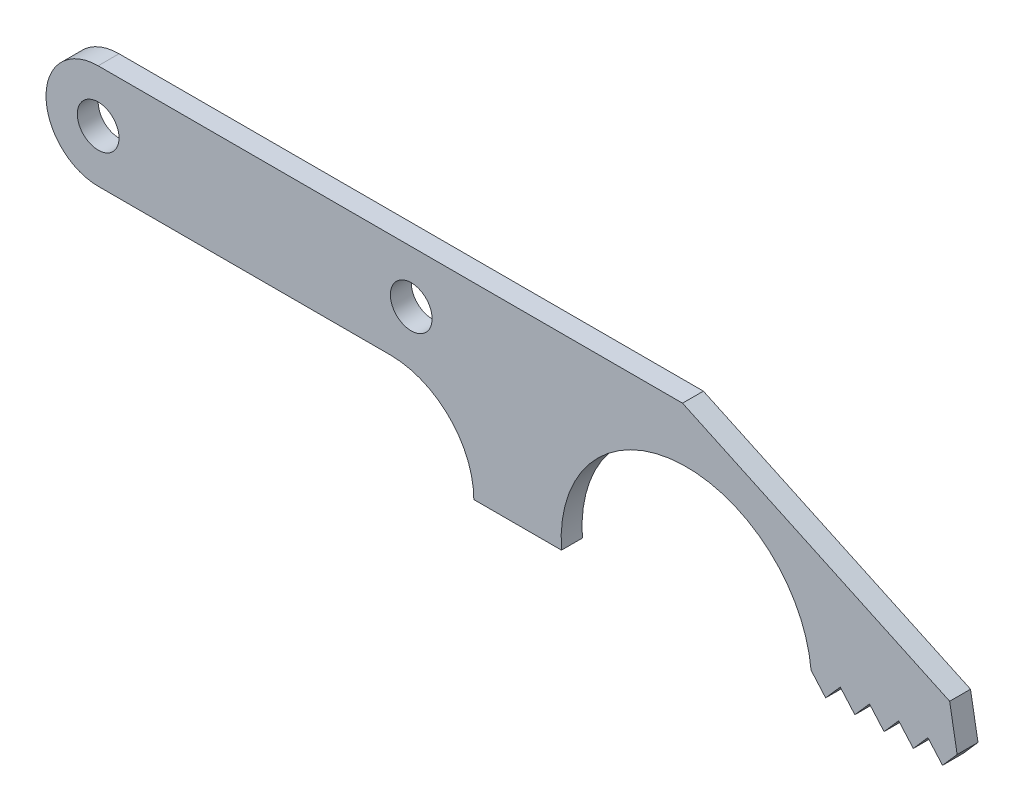
SolidWorks part; units mm, degrees
ref_plane "Front Plane" through (0, 0, 0) normal (0, 0, 1) x (1, 0, 0)
ref_plane "Top Plane" through (0, 0, 0) normal (0, 1, 0) x (1, 0, 0)
ref_plane "Right Plane" through (0, 0, 0) normal (1, 0, 0) x (0, 0, -1)
sketch "Sketch1" plane through (0, 0, 0) normal (0, 0, 1) x (1, 0, 0)
  line L0 (0, 0) -> (0, 25) construction
  line L1 (0, 25) -> (140, 25)
  line L2 (140, 25) -> (203.9984, -4.8429)
  line L3 (203.9984, -4.8429) -> (205.7894, -15)
  line L4 (205.7894, -15) -> (170.7894, -15) construction
  line L5 (0, 0) -> (70, 0)
  line L6 (90, -20) -> (111, -20)
  line L7 (0, 12.5) -> (75, 12.5) construction
  line L8 (90, -20) -> (93.5, -24)
  line L9 (93.5, -24) -> (97, -20)
  line L10 (97, -20) -> (100.5, -24)
  line L11 (100.5, -24) -> (104, -20)
  line L12 (104, -20) -> (107.5, -24)
  line L13 (107.5, -24) -> (111, -20)
  line L14 (170.7894, -15) -> (174.2894, -19)
  line L15 (174.2894, -19) -> (177.7894, -15)
  line L16 (177.7894, -15) -> (181.2894, -19)
  line L17 (181.2894, -19) -> (184.7894, -15)
  line L18 (184.7894, -15) -> (188.2894, -19)
  line L19 (188.2894, -19) -> (191.7894, -15)
  line L20 (191.7894, -15) -> (195.2894, -19)
  line L21 (195.2894, -19) -> (198.7894, -15)
  line L22 (198.7894, -15) -> (202.2894, -19)
  line L23 (202.2894, -19) -> (205.7894, -15)
  arc A0 (70, 0) -> (90, -20) centre (70, -20) cw
  arc A1 (111, -20) -> (170.7894, -15) centre (140.9148, -17.7405) cw
  arc A2 (0, 25) -> (0, 0) centre (0, 12.5) ccw
  circle A3 centre (0, 12.5) radius 5
  circle A4 centre (75, 12.5) radius 5
  dimension "D8" = 20
  dimension "D10" = 10
  dimension "D11" = 10
  dimension "D1" = 25
  dimension "D2" = 140
  dimension "D3" = 205
  dimension "D4" = 100
  dimension "D5" = 35
  dimension "D6" = 15
  dimension "D7" = 70
  dimension "D9" = 21
  dimension "D12" = 75
  dimension "D13" = 4
  dimension "D14" = 3.5
  dimension "D15" = 3.5
  dimension "D17" = 4
  dimension "D18" = 3.5
  dimension "D19" = 3.5
  dimension "D16" = 3
  dimension "D20" = 5
extrude "Boss-Extrude1" add sketch "Sketch1" along normal mid plane 5 contours L1 A2 L5 A0 L6 A1 L14 L15 L16 L17 L18 L19 L20 L21 L22 L23 L3 L2 A4 A3
